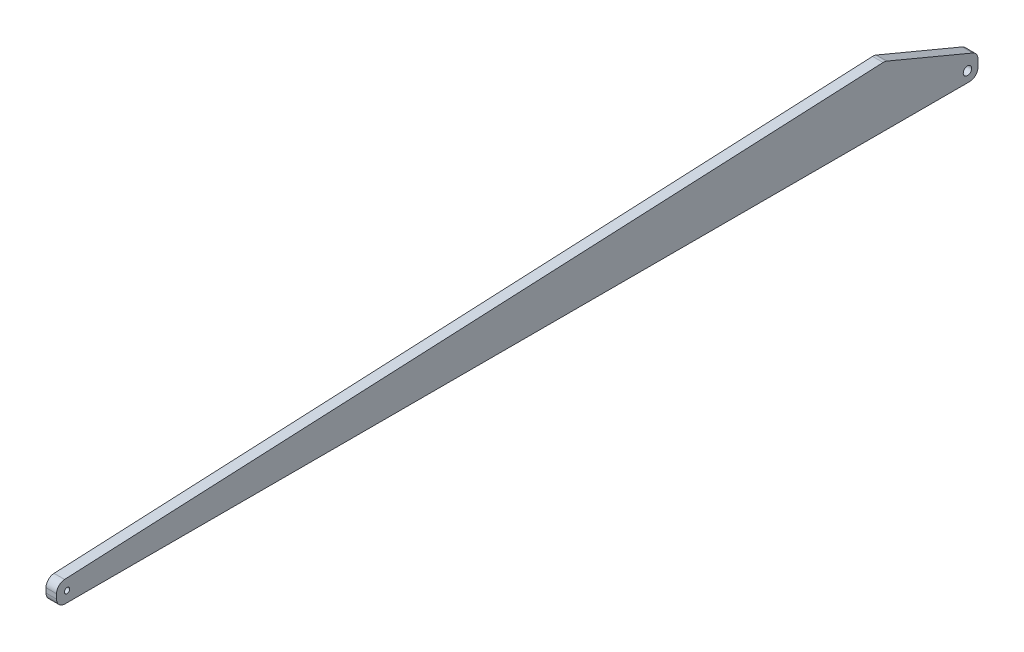
SolidWorks part; units mm, degrees
material "AISI 1010 Steel, hot rolled bar"
ref_plane "Front Plane" through (0, 0, 0) normal (0, 0, 1) x (1, 0, 0)
ref_plane "Top Plane" through (0, 0, 0) normal (0, 1, 0) x (1, 0, 0)
ref_plane "Right Plane" through (0, 0, 0) normal (1, 0, 0) x (0, 0, -1)
sketch "Sketch3" plane through (0, 0, 0) normal (1, 0, 0) x (0, 0, -1)
  line L0 (-265.049, 0) -> (265.049, 0)
  line L1 (-277.749, 0) -> (-277.749, 12.7)
  line L2 (277.749, 0) -> (277.749, 12.7)
  line L3 (-265.049, 0) -> (-277.749, 0)
  line L4 (265.049, 0) -> (277.749, 0)
  line L5 (221.6876, 0) -> (221.6876, 36.1531) construction
  line L6 (-277.749, 12.7) -> (221.6876, 36.1531)
  line L7 (221.6876, 36.1531) -> (277.749, 12.7)
  circle A0 centre (-271.399, 6.35) radius 1.6002
  circle A1 centre (271.399, 6.35) radius 2.5527
  point P8 (0, 0)
  point P14 (221.6876, 36.1531)
  dimension "D5" = 12.7
  dimension "D1" = 530.098
  dimension "D2" = 12.7
  dimension "D3" = 12.7
  dimension "D4" = 12.7
  dimension "D6" = 6.35
  dimension "D7" = 6.35
  dimension "D8" = 6.35
  dimension "D9" = 6.35
extrude "Boss-Extrude1" add sketch "Sketch3" along normal blind 6.35
fillet "Fillet1" radius 5.08 5 edges at (3.175, 0, -277.749) (3.175, 12.7, -277.749) (3.175, 36.1531, -221.6876) (3.175, 0, 277.749) (3.175, 12.7, 277.749)
